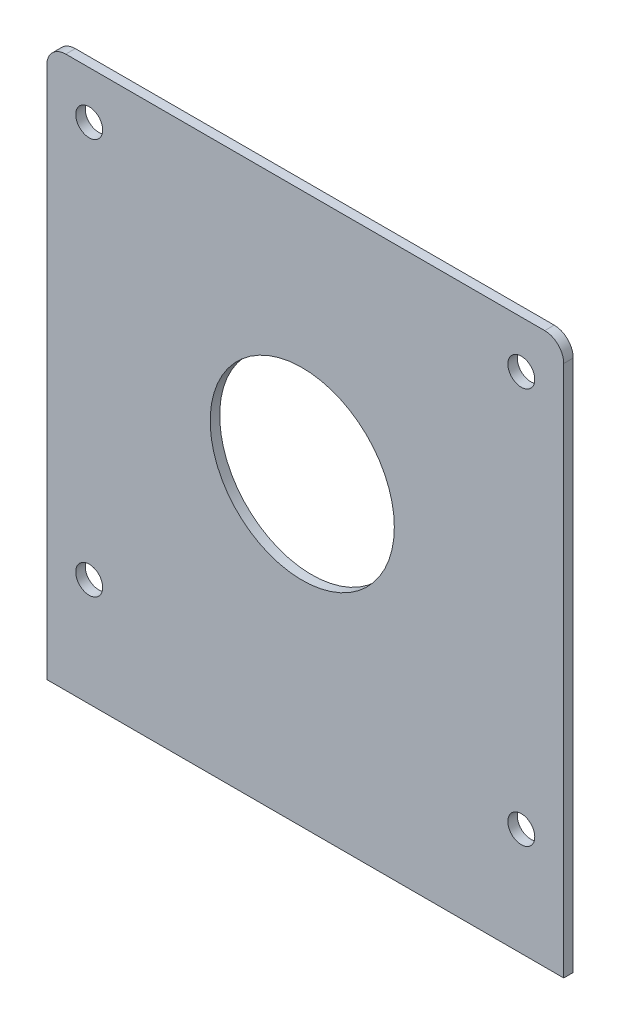
SolidWorks part; units mm, degrees
material "ASTM A36 Steel"
ref_plane "X-Y Datum" through (0, 0, 0) normal (0, 0, 1) x (1, 0, 0)
ref_plane "X-Z Datum" through (0, 0, 0) normal (0, 1, 0) x (1, 0, 0)
ref_plane "Y-Z Datum" through (0, 0, 0) normal (1, 0, 0) x (0, 0, -1)
sketch "Sketch2" plane through (0, 0, 0) normal (0, 0, 1) x (1, 0, 0)
  line L0 (43.18, 42.8625) -> (-43.18, 42.8625)
  line L2 (-43.18, 42.8625) -> (-43.18, -42.8625)
  line L4 (-43.18, 42.8625) -> (0, 0) construction
  line L5 (-43.18, -42.8625) -> (0, 0) construction
  line L6 (-43.18, -42.8625) -> (43.18, -42.8625)
  line L7 (43.18, -42.8625) -> (43.18, 42.8625)
  line L8 (0, 0) -> (43.18, -42.8625) construction
  line L9 (0, 0) -> (43.18, 42.8625) construction
  dimension "D1" = 86.36
  dimension "D3" = 85.725
extrude "Boss-Extrude1" add sketch "Sketch2" along normal mid plane 1.5875
sketch "Sketch3" plane through (0, 0, 0.7937) normal (0, 0, 1) x (1, 0, 0)
  circle A0 centre (-0.5, 1.8625) radius 15 construction
  circle A3 centre (-36.0914, -31.2289) radius 3.025 construction
  circle A4 centre (36.0914, -31.2289) radius 3.025 construction
  circle A5 centre (-36.0914, 34.9539) radius 3.025 construction
  circle A6 centre (36.0914, 34.9539) radius 3.025 construction
  circle A7 centre (-36.0914, -31.2289) radius 3.025 construction
  circle A8 centre (36.0914, -31.2289) radius 3.025 construction
  circle A9 centre (-36.0914, 34.9539) radius 3.025 construction
  circle A10 centre (36.0914, 34.9539) radius 3.025 construction
  circle A11 centre (-0.5, 1.8625) radius 15.381
  circle A12 centre (-0.5, 1.8625) radius 15 construction
  point P3 (36.0914, -31.2289)
  point P4 (-36.0914, -31.2289)
  point P6 (-36.0914, 34.9539)
  point P8 (36.0914, 34.9539)
  point P24 (-0.5, 1.8625)
  dimension "D1" = 30.762
  dimension "D2" = 30
  dimension "D3" = 0.381
extrude "Cut-Extrude1" cut sketch "Sketch3" against normal through all
hole_wizard "M4 Clearance Hole1" positions "3DSketch1" profile "Sketch4" hole size "M4" standard "ANSI Metric" end condition through all
sketch3d "3DSketch1"
  point P0 (36.0914, 34.9539, 0.7937)
  point P3 (36.0914, -31.2289, 0.7937)
  point P6 (-36.0914, 34.9539, 0.7937)
  point P9 (-36.0914, -31.2289, 0.7937)
sketch "Sketch4" plane through (36.0914, 34.9539, 0.7937) normal (1, 0, 0) x (0, -1, 0)
  line L0 (0, 0) -> (0, 1.5875)
  line L1 (0, 1.5875) -> (2.25, 1.5875)
  line L2 (2.25, 1.5875) -> (2.25, 0)
  line L5 (2.25, 0) -> (0, 0)
  line L11 (0, -6.35) -> (0, 107.95) construction
  dimension "Thru Hole Dia." = 4.5
  dimension "Thru Hole Depth" = 1.5875
sketch "Sketch5" plane through (0, 0, 0.7937) normal (0, 0, 1) x (1, 0, 0)
  line L0 (-43.18, 42.8625) -> (-43.18, -42.8625) construction
  line L1 (43.18, -42.8625) -> (-43.18, -42.8625)
  line L2 (43.18, -42.8625) -> (43.18, -49.2125)
  line L3 (43.18, -49.2125) -> (-43.18, -49.2125)
  line L4 (-43.18, -42.8625) -> (-43.18, -49.2125)
  dimension "D1" = 6.35
extrude "Boss-Extrude2" add sketch "Sketch5" against normal blind 1.5875
fillet "Fillet1" radius 3.175 2 edges at (-43.18, 42.8625, 0) (43.18, 42.8625, 0)
